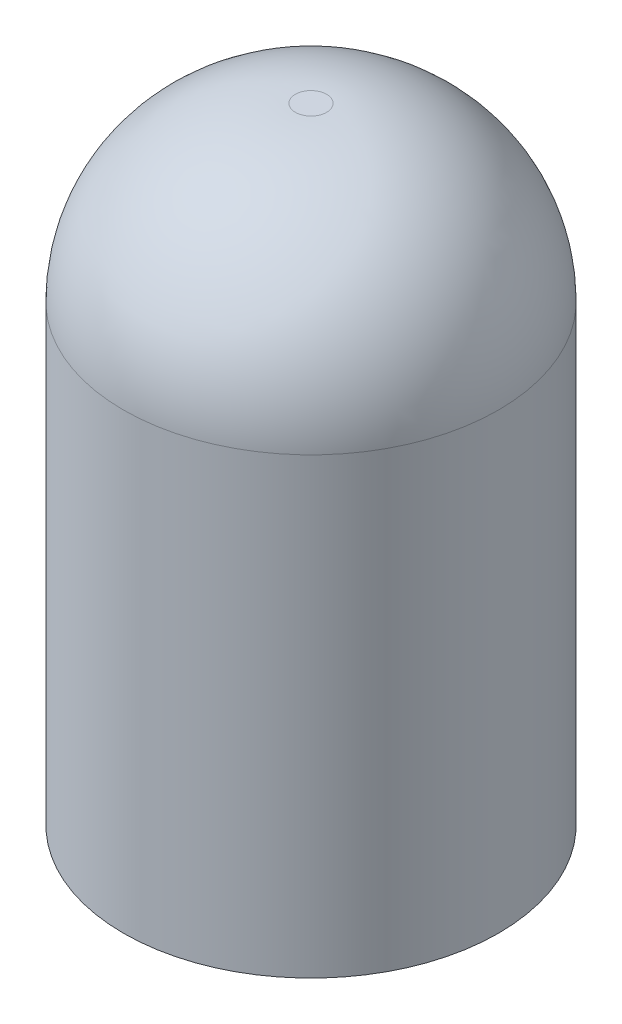
SolidWorks part; units mm, degrees
ref_plane "Front Plane" through (0, 0, 0) normal (0, 0, 1) x (1, 0, 0)
ref_plane "Top Plane" through (0, 0, 0) normal (0, 1, 0) x (1, 0, 0)
ref_plane "Right Plane" through (0, 0, 0) normal (1, 0, 0) x (0, 0, -1)
sketch "Sketch1" plane through (0, 0, 0) normal (0, 0, 1) x (1, 0, 0)
  line L0 (0, 0) -> (60, 0)
  line L1 (60, 0) -> (60, 145)
  line L2 (5, 200) -> (0, 200)
  line L3 (0, 200) -> (0, 0)
  arc A0 (60, 145) -> (5, 200) centre (5, 145) ccw
  dimension "D1" = 200
  dimension "D2" = 60
  dimension "D3" = 145
revolve "Revolve1" add sketch "Sketch1" angle 360 about L3
shell "Shell1" thickness 2
